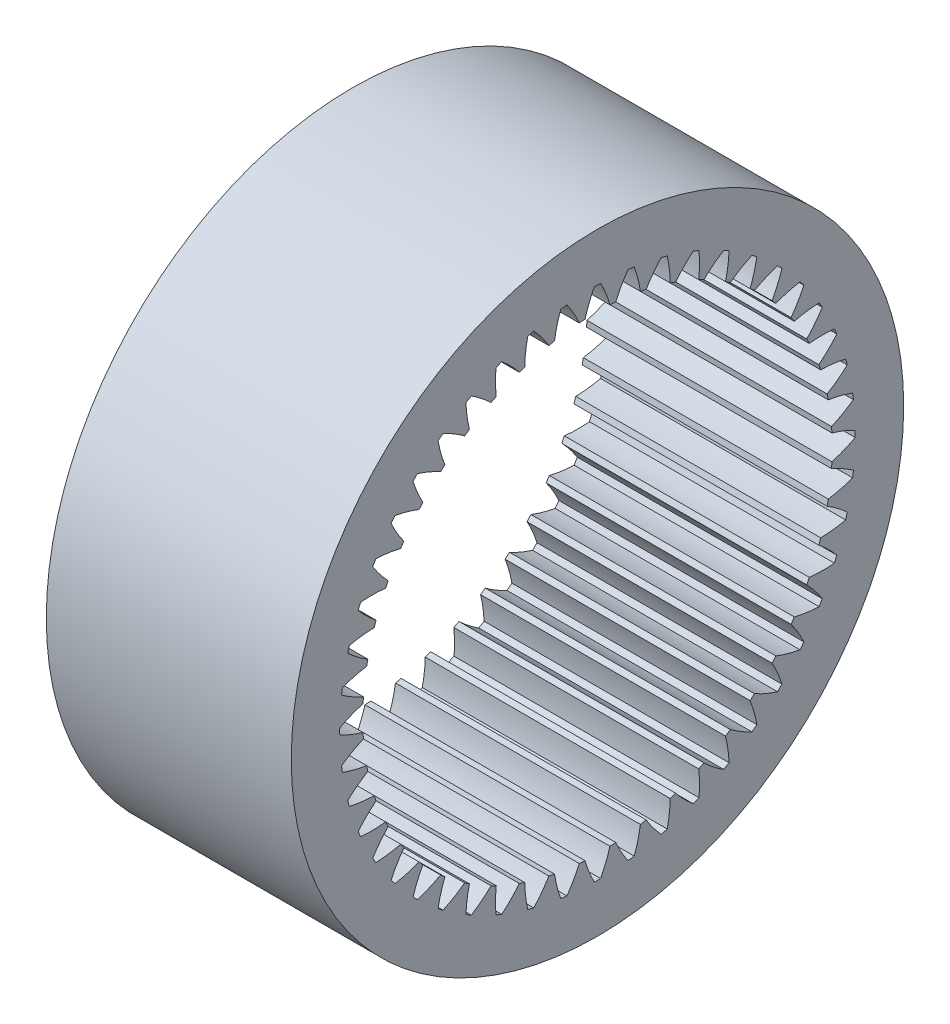
SolidWorks part; units mm, degrees
ref_plane "Plane1" through (0, 0, 0) normal (0, 0, 1) x (1, 0, 0)
ref_plane "Plane2" through (0, 0, 0) normal (0, 1, 0) x (1, 0, 0)
ref_plane "Plane3" through (0, 0, 0) normal (1, 0, 0) x (0, 0, -1)
other "Configuration Table"
sketch "HoldingSke" plane through (0, 0, 0) normal (0, 1, 0) x (1, 0, 0)
  line L0 (0, 0) -> (1.3383, -1.4863)
  line L1 (-15, 0) -> (100, 0) construction
  line L2 (0, 0) -> (-2.1039, 2.3779)
  line L3 (0, 0) -> (-11.863, 4.5341)
  line L4 (0, 0) -> (5.7786, 6.4178)
  line L5 (0, 0) -> (-23.7986, -8.8762)
  line L6 (0, 0) -> (-10.5278, -7.1032)
  line L7 (-2.1039, 2.3779) -> (3.3635, 27.1825)
  line L8 (-76.2, 2.8779) -> (-54.61, 2.8779)
  line L9 (-71.009, 38.7566) -> (-53.1078, 45.2721)
  line L10 (-76.2, 71.12) -> (104.1128, 71.12)
  line L11 (0, 0) -> (-12, 0)
  line L12 (-76.2, 101.6) -> (-76.181, 101.6)
  line L13 (24.9733, 27.94) -> (52.9518, 28.4284)
  line L14 (24.9733, 27.94) -> (24.9743, 27.94)
  line L15 (24.9733, 27.94) -> (100.4006, 29.5858)
  circle A0 centre (0, 0) radius 15
  circle A1 centre (0, 0) radius 12.7
  circle A2 centre (0, 0) radius 12.7
  dimension "MHD" = 25.4
  dimension "Hub_dia" = 25.4
  dimension "Diameter" = 30
  dimension "Num_teeth" = 48
  dimension "Pitch" = 2
  dimension "Overall_len" = 25.4
  dimension "Show_teeth" = 48
  dimension "Thickness" = 12.7
  dimension "OAL" = 25.4001
  dimension "T_dim" = 21.59
  dimension "Ap" = 20
  dimension "H" = 19.05
  dimension "Pitch_radius" = 180.3128
  dimension "Width" = 12
  dimension "Backlash" = 0.019
  dimension "Addendum_fac" = 1
  dimension "Dedendum_fac" = 1.25
  dimension "Clearance_fac" = 0.25
  dimension "Dedendum_add" = 0.001
  dimension "Module" = 0.5
sketch "BasProSke" plane through (0, 0, 0) normal (0, 1, 0) x (1, 0, 0)
  line L0 (-10, 0) -> (60, 0) construction
  line L1 (0, 11.5) -> (0, 15)
  line L2 (0, 11.5) -> (12, 11.5)
  line L3 (12, 11.5) -> (12, 15)
  line L4 (12, 15) -> (0, 15)
  dimension "Diameter" = 30
  dimension "Thickness" = 12
  dimension "Inside_diameter" = 23
revolve "Base-Revolve" add sketch "BasProSke" angle 360 about L0
sketch "TooCutSke" plane through (0, 0, 0) normal (1, 0, 0) x (0, 0, -1)
  line L3 (0.4401, 11.9919) -> (0.4401, 53.6633) construction
  line L4 (0, 0) -> (0, 59.563) construction
  line L5 (0, 0) -> (-4.4688, 68.1812) construction
  line L6 (-5.1578, 9.8324) -> (37.098, 12.602) construction
  circle A0 centre (0, 0) radius 12 construction
  circle A1 centre (0, 0) radius 12.626 construction
  circle A2 centre (0, 0) radius 10.1487 construction
  circle A3 centre (0, 0) radius 11.4746 construction
  arc A4 (0.6178, 11.458) -> (0.1527, 12.6251) centre (-5.1578, 9.8324) ccw
  arc A5 (0.6178, 11.458) -> (-0.6178, 11.458) centre (0, 0) ccw
  arc A6 (0.1527, 12.6251) -> (-0.1527, 12.6251) centre (0, 0) ccw
  arc A7 (-0.1527, 12.6251) -> (-0.6178, 11.458) centre (5.1578, 9.8324) ccw
  dimension "Pitch_dia" = 24
  dimension "Base_dia" = 20.2974
  dimension "Root_dia" = 25.252
  dimension "Overcut_dia" = 22.9492
  dimension "Flank_rad" = 6
  dimension "Half_ang" = 3.75
  dimension "Half_CT" = 0.4401
extrude "ToothCut" cut sketch "TooCutSke" along normal through all
fillet "Breaks" [suppressed] radius 0.05
fillet "RootFillets" [suppressed] radius 0.126
pattern_circular "TeethCuts" count 48 every 7.5 about axis through (-10, 0, 0) along (1, 0, 0) of "RootFillets", "Breaks", "ToothCut"
equation "' \"Module@HoldingSke\" = 6.35"
equation "' \"Num_teeth@HoldingSke\" = 24"
equation "' \"Ap@HoldingSke\" =  14.5"
equation "' \"Ap@HoldingSke\" = 14.5"
equation "' \"Width@HoldingSke\" = 12"
equation "' \"Diameter@HoldingSke\" = 8 * 25.4"
equation "' \"Show_teeth@HoldingSke\" = 100"
equation "' \"Backlash@HoldingSke\" = 0.009 * 25.4"
equation "' \"Addendum_fac@HoldingSke\" = 1.0"
equation "' \"Dedendum_fac@HoldingSke\" = 1.25"
equation "' \"Dedendum_add@HoldingSke\" = 0.00005 * 25.4"
equation "' \"Clearance_fac@HoldingSke\" = 0.25"
equation "\"Pitch@HoldingSke\" = 1 / \"Module@HoldingSke\" "
equation "\"Overcut_dia@TooCutSke\" = (\"Num_teeth@HoldingSke\" - 2 * \"Addendum_fac@HoldingSke\") / \"Pitch@HoldingSke\" - 0.002 * 25.4"
equation "\"Pitch_dia@TooCutSke\" = \"Num_teeth@HoldingSke\" / \"Pitch@HoldingSke\""
equation "\"Base_dia@TooCutSke\" = \"Num_teeth@HoldingSke\" / \"Pitch@HoldingSke\" * cos((\"Ap@HoldingSke\"  * 3.14159265 / 180)) * 0.90"
equation "\"Root_dia@TooCutSke\" = \"Num_teeth@HoldingSke\"  / \"Pitch@HoldingSke\" + 2 *  \"Dedendum_fac@HoldingSke\"/ \"Pitch@HoldingSke\" + \"Dedendum_add@HoldingSke\" * 2"
equation "\"Half_ang@TooCutSke\" = 180 / \"Num_teeth@HoldingSke\""
equation "\"Half_CT@TooCutSke\" = \"Num_teeth@HoldingSke\" / \"Pitch@HoldingSke\" * sin((3.14159265 / 2 / \"Num_teeth@HoldingSke\")) / 2 + 10 * \"Backlash@HoldingSke\" / 4"
equation "\"Flank_rad@TooCutSke\" = \"Num_teeth@HoldingSke\" / \"Pitch@HoldingSke\" / 4"
equation "\"Radius@RootFillets\"= \"Clearance_fac@HoldingSke\" / \"Pitch@HoldingSke\" + \"Dedendum_add@HoldingSke\""
equation "\"Break_rad@Breaks\" = 0.02 / \"Pitch@HoldingSke\" * 5"
equation "\"Num_teeth@TeethCuts\" = int( \"Show_teeth@HoldingSke\" ) + 1"
equation "\"Num_teeth@TeethCuts\" = ((sgn( \"Num_teeth@TeethCuts\" - \"Num_teeth@HoldingSke\" )-1)*( \"Num_teeth@TeethCuts\" - \"Num_teeth@HoldingSke\" ))/-2+ \"Num_teeth@HoldingSke\""
equation "\"Num_teeth@TeethCuts\" = ((sgn( \"Num_teeth@TeethCuts\" - 2.0)+1)*( \"Num_teeth@TeethCuts\" - 2.0))/2 +2.0"
equation "\"Angle@TeethCuts\" = 360.0 / \"Num_teeth@HoldingSke\""
equation "\"Diameter@BasProSke\" = \"Num_teeth@HoldingSke\"  / \"Pitch@HoldingSke\" + 2 *  \"Dedendum_fac@HoldingSke\"/ \"Pitch@HoldingSke\" + \"Dedendum_add@HoldingSke\" * 2 + 0.002 * 25.4"
equation "\"Diameter@BasProSke\" = ((sgn( \"Diameter@BasProSke\"  - \"Diameter@HoldingSke\" )+1)*( \"Diameter@BasProSke\"  - \"Diameter@HoldingSke\" ))/2 + \"Diameter@HoldingSke\""
equation "\"Inside_diameter@BasProSke\" =  (\"Num_teeth@HoldingSke\" - 2 * \"Addendum_fac@HoldingSke\") / \"Pitch@HoldingSke\" "
equation "\"Thickness@BasProSke\"  = \"Width@HoldingSke\""
